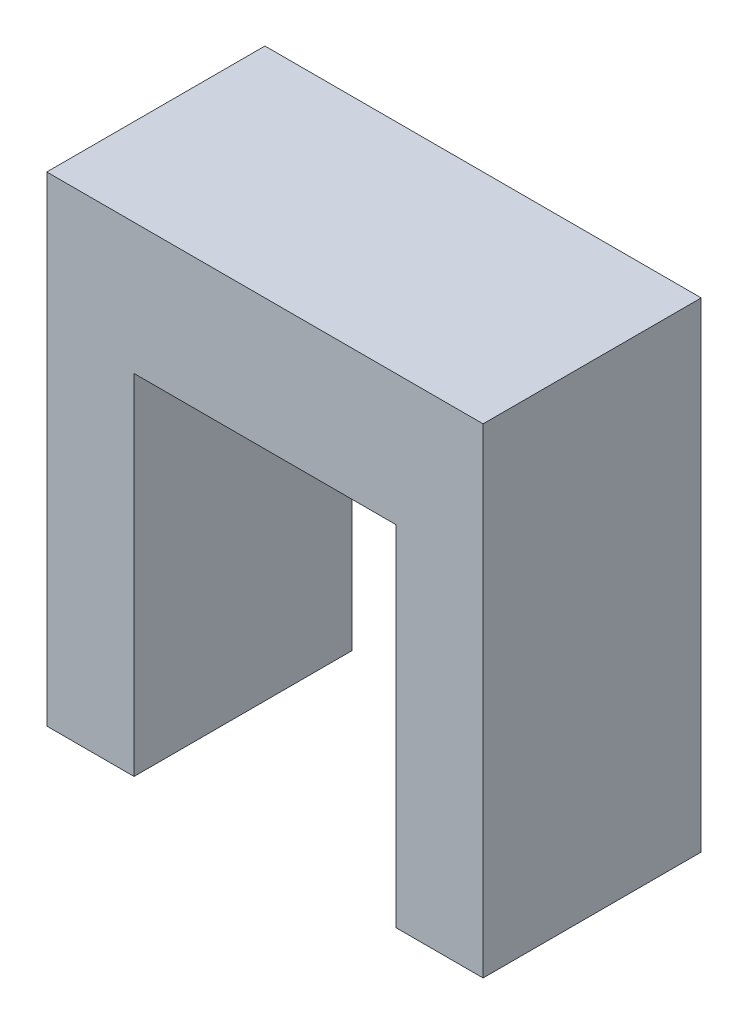
SolidWorks part; units mm, degrees
ref_plane "Front Plane" through (0, 0, 0) normal (0, 0, 1) x (1, 0, 0)
ref_plane "Top Plane" through (0, 0, 0) normal (0, 1, 0) x (1, 0, 0)
ref_plane "Right Plane" through (0, 0, 0) normal (1, 0, 0) x (0, 0, -1)
sketch "Sketch1" plane through (0, 0, 0) normal (0, 0, 1) x (1, 0, 0)
  line L1 (-25, 0) -> (25, 0)
  line L2 (-25, 0) -> (-25, 15)
  line L3 (-25, 15) -> (25, 15)
  line L4 (25, 0) -> (25, 15)
extrude "Boss-Extrude1" add sketch "Sketch1" along normal blind 25
sketch "Sketch2" plane through (0, 0, 0) normal (0, 0, 1) x (1, 0, 0)
  line L1 (-25, -40) -> (-15, -40)
  line L2 (-25, -40) -> (-25, 1)
  line L3 (-25, 1) -> (-15, 1)
  line L4 (-15, -40) -> (-15, 1)
extrude "Boss-Extrude2" add sketch "Sketch2" along normal blind 25
sketch "Sketch3" plane through (0, 0, 0) normal (0, 0, 1) x (1, 0, 0)
  line L0 (25, 0) -> (25, 15) construction
  line L1 (15, -40) -> (25, -40)
  line L2 (15, -40) -> (15, 1)
  line L3 (15, 1) -> (25, 1)
  line L4 (25, -40) -> (25, 1)
extrude "Boss-Extrude3" add sketch "Sketch3" along normal blind 25
